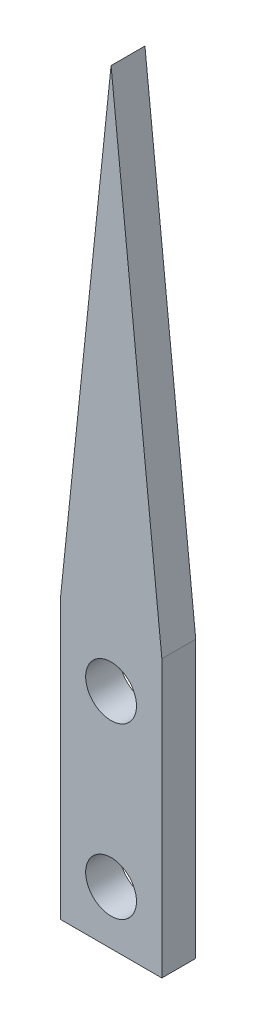
SolidWorks part; units mm, degrees
ref_plane "前视基准面" through (0, 0, 0) normal (0, 0, 1) x (1, 0, 0)
ref_plane "上视基准面" through (0, 0, 0) normal (0, 1, 0) x (1, 0, 0)
ref_plane "右视基准面" through (0, 0, 0) normal (1, 0, 0) x (0, 0, -1)
sketch "草图1" plane through (0, 0, 0) normal (0, 0, 1) x (1, 0, 0)
  line L0 (0, 0) -> (0, -10) construction
  line L1 (0, -10) -> (0, 32) construction
  line L2 (3, 3.1642) -> (0, 32)
  line L3 (3, 3.1642) -> (-3, 3.1642) construction
  line L4 (3, 3.1642) -> (3, -13.1642)
  line L5 (3, -13.1642) -> (-3, -13.1642)
  line L6 (-3, 3.1642) -> (-3, -13.1642)
  line L7 (3, 3.1642) -> (-3, -13.1642) construction
  line L8 (3, -13.1642) -> (-3, 3.1642) construction
  line L9 (0, 32) -> (-3, 3.1642)
  circle A0 centre (0, 0) radius 1.5
  circle A1 centre (0, -10) radius 1.5
  point P7 (0, -5)
extrude "凸台-拉伸1" add sketch "草图1" along normal blind 2
